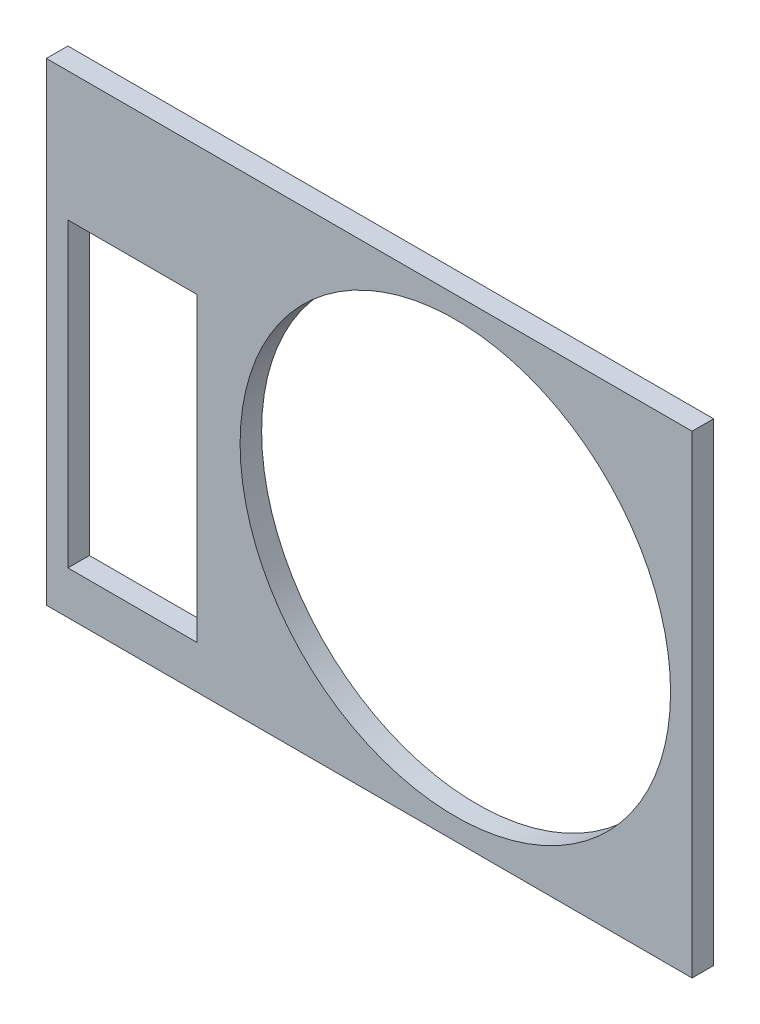
SolidWorks part; units mm, degrees
ref_plane "Alzado" through (0, 0, 0) normal (0, 0, 1) x (1, 0, 0)
ref_plane "Planta" through (0, 0, 0) normal (0, 1, 0) x (1, 0, 0)
ref_plane "Vista lateral" through (0, 0, 0) normal (1, 0, 0) x (0, 0, -1)
sketch "Croquis1" plane through (0, 0, 0) normal (0, 0, 1) x (1, 0, 0)
  line L1 (0, 0) -> (300, 0)
  line L2 (0, 0) -> (0, 220)
  line L3 (0, 220) -> (300, 220)
  line L4 (300, 0) -> (300, 220)
  circle A0 centre (190, 110) radius 100
  dimension "D3" = 200
  dimension "D4" = 110
  dimension "D5" = 110
  dimension "D1" = 300
  dimension "D2" = 220
extrude "Saliente-Extruir1" add sketch "Croquis1" along normal blind 10
sketch "Croquis2" plane through (0, 0, 10) normal (0, 0, 1) x (1, 0, 0)
  line L0 (0, 0) -> (300, 0) construction
  line L1 (70, 20) -> (10, 20)
  line L2 (70, 20) -> (70, 160)
  line L3 (70, 160) -> (10, 160)
  line L4 (10, 20) -> (10, 160)
  circle A0 centre (190, 110) radius 100 construction
  dimension "D1" = 60
  dimension "D2" = 140
  dimension "D3" = 20
  dimension "D4" = 120
extrude "Cortar-Extruir1" cut sketch "Croquis2" against normal blind 10
